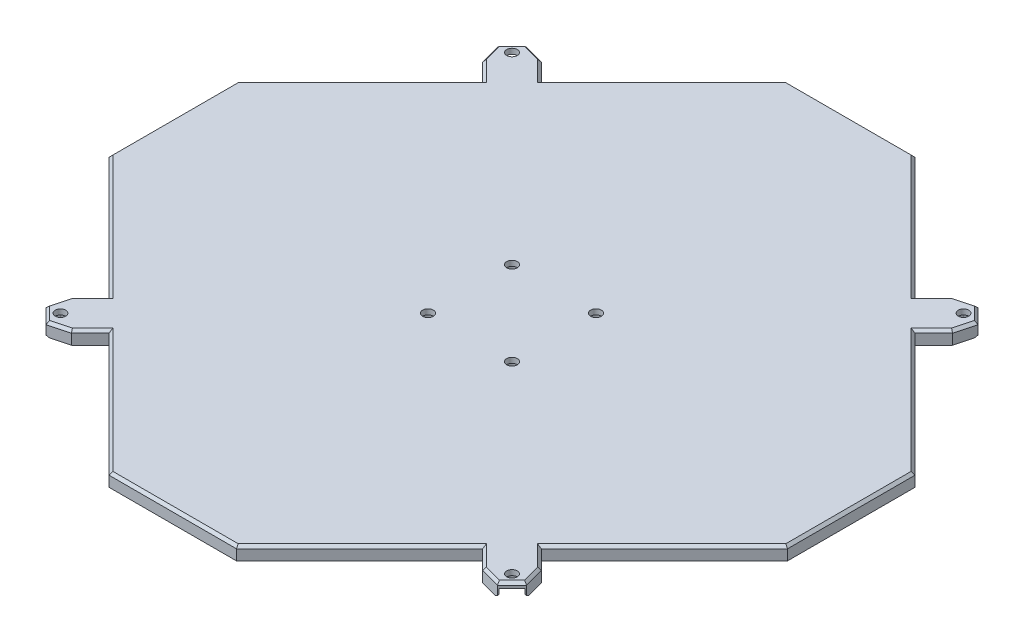
SolidWorks part; units mm, degrees
material "ABS"
ref_plane "Front Plane" through (0, 0, 0) normal (0, 0, 1) x (1, 0, 0)
ref_plane "Top Plane" through (0, 0, 0) normal (0, 1, 0) x (1, 0, 0)
ref_plane "Right Plane" through (0, 0, 0) normal (1, 0, 0) x (0, 0, -1)
sketch "Floor Reference" plane through (0, 0, 0) normal (0, 1, 0) x (-1, 0, 0)
  line L0 (-129.3223, 24.3223) -> (-82.4792, 71.1655)
  line L1 (-82.4792, 71.1655) -> (-89.601, 78.2873)
  line L2 (-89.601, 78.2873) -> (-91.6716, 86.0147)
  line L3 (-91.6716, 86.0147) -> (-86.0147, 91.6716)
  line L4 (-86.0147, 91.6716) -> (-78.2873, 89.601)
  line L5 (-78.2873, 89.601) -> (-71.1655, 82.4792)
  line L6 (-71.1655, 82.4792) -> (-24.3223, 129.3223)
  line L7 (-24.3223, 129.3223) -> (0, 129.3223)
  line L31 (-129.3223, 0) -> (-129.3223, 24.3223)
  line L32 (0, 0) -> (-35355.3391, 35355.3391) construction
  line L34 (-1000, 0) -> (0, 0) construction
  line L35 (0, 0) -> (0, 49000) construction
  circle A0 centre (-86.0147, 86.0147) radius 2
  point P8 (0, 0)
  point P14 (0, 0)
  point P18 (-88.8431, 88.8431)
  dimension "D11" = 4
  dimension "D1" = 105
  dimension "D2" = 45
  dimension "D3" = 129.3223
  dimension "D4" = 8
  dimension "D5" = 16
  dimension "D6" = 17
  dimension "D7" = 8
  dimension "D8" = 13
  dimension "D9" = 105
  dimension "D10" = 24.3223
sketch "Sketch2" plane through (0, 0, 0) normal (0, 1, 0) x (1, 0, 0)
  line L0 (129.3223, 0) -> (129.3223, -24.3223) construction
  line L1 (129.3223, -24.3223) -> (82.4792, -71.1655) construction
  line L2 (82.4792, -71.1655) -> (89.601, -78.2873) construction
  line L3 (89.601, -78.2873) -> (91.6716, -86.0147) construction
  line L4 (91.6716, -86.0147) -> (86.0147, -91.6716) construction
  line L5 (86.0147, -91.6716) -> (78.2873, -89.601) construction
  line L6 (78.2873, -89.601) -> (71.1655, -82.4792) construction
  line L7 (71.1655, -82.4792) -> (24.3223, -129.3223) construction
  line L8 (24.3223, -129.3223) -> (0, -129.3223) construction
  line L9 (129.3223, 0) -> (129.3223, -24.3223) construction
  line L10 (129.3223, -24.3223) -> (82.4792, -71.1655) construction
  line L11 (82.4792, -71.1655) -> (89.601, -78.2873) construction
  line L12 (89.601, -78.2873) -> (91.6716, -86.0147) construction
  line L13 (91.6716, -86.0147) -> (86.0147, -91.6716) construction
  line L14 (86.0147, -91.6716) -> (78.2873, -89.601) construction
  line L15 (78.2873, -89.601) -> (71.1655, -82.4792) construction
  line L16 (71.1655, -82.4792) -> (24.3223, -129.3223) construction
  line L17 (24.3223, -129.3223) -> (0, -129.3223) construction
  line L18 (-129.3223, -24.3223) -> (-129.3223, 0) construction
  line L19 (-82.4792, -71.1655) -> (-129.3223, -24.3223) construction
  line L20 (-89.601, -78.2873) -> (-82.4792, -71.1655) construction
  line L21 (-91.6716, -86.0147) -> (-89.601, -78.2873) construction
  line L22 (-86.0147, -91.6716) -> (-91.6716, -86.0147) construction
  line L23 (-78.2873, -89.601) -> (-86.0147, -91.6716) construction
  line L24 (-71.1655, -82.4792) -> (-78.2873, -89.601) construction
  line L25 (-24.3223, -129.3223) -> (-71.1655, -82.4792) construction
  line L26 (0, -129.3223) -> (-24.3223, -129.3223) construction
  line L27 (-24.3223, 129.3223) -> (0, 129.3223) construction
  line L28 (-71.1655, 82.4792) -> (-24.3223, 129.3223) construction
  line L29 (-78.2873, 89.601) -> (-71.1655, 82.4792) construction
  line L30 (-86.0147, 91.6716) -> (-78.2873, 89.601) construction
  line L31 (-91.6716, 86.0147) -> (-86.0147, 91.6716) construction
  line L32 (-89.601, 78.2873) -> (-91.6716, 86.0147) construction
  line L33 (-82.4792, 71.1655) -> (-89.601, 78.2873) construction
  line L34 (-129.3223, 24.3223) -> (-82.4792, 71.1655) construction
  line L35 (-129.3223, 0) -> (-129.3223, 24.3223) construction
  line L36 (129.3223, 24.3223) -> (129.3223, 0) construction
  line L37 (82.4792, 71.1655) -> (129.3223, 24.3223) construction
  line L38 (89.601, 78.2873) -> (82.4792, 71.1655) construction
  line L39 (91.6716, 86.0147) -> (89.601, 78.2873) construction
  line L40 (86.0147, 91.6716) -> (91.6716, 86.0147) construction
  line L41 (78.2873, 89.601) -> (86.0147, 91.6716) construction
  line L42 (71.1655, 82.4792) -> (78.2873, 89.601) construction
  line L43 (24.3223, 129.3223) -> (71.1655, 82.4792) construction
  line L44 (0, 129.3223) -> (24.3223, 129.3223) construction
  line L45 (129.2223, 0) -> (129.2223, -24.2809)
  line L46 (129.2223, -24.2809) -> (82.3378, -71.1655)
  line L47 (82.3378, -71.1655) -> (89.5114, -78.3391)
  line L48 (89.5114, -78.3391) -> (91.56, -85.9848)
  line L49 (91.56, -85.9848) -> (85.9848, -91.56)
  line L50 (85.9848, -91.56) -> (78.3391, -89.5114)
  line L51 (78.3391, -89.5114) -> (71.1655, -82.3378)
  line L52 (71.1655, -82.3378) -> (24.2809, -129.2223)
  line L53 (24.2809, -129.2223) -> (0, -129.2223)
  line L54 (0, -129.2223) -> (-24.2809, -129.2223)
  line L55 (-24.2809, -129.2223) -> (-71.1655, -82.3378)
  line L56 (-71.1655, -82.3378) -> (-78.3391, -89.5114)
  line L57 (-78.3391, -89.5114) -> (-85.9848, -91.56)
  line L58 (-85.9848, -91.56) -> (-91.56, -85.9848)
  line L59 (-91.56, -85.9848) -> (-89.5114, -78.3391)
  line L60 (-89.5114, -78.3391) -> (-82.3378, -71.1655)
  line L61 (-82.3378, -71.1655) -> (-129.2223, -24.2809)
  line L62 (-129.2223, -24.2809) -> (-129.2223, 0)
  line L63 (-129.2223, 0) -> (-129.2223, 24.2809)
  line L64 (-129.2223, 24.2809) -> (-82.3378, 71.1655)
  line L65 (-82.3378, 71.1655) -> (-89.5114, 78.3391)
  line L66 (-89.5114, 78.3391) -> (-91.56, 85.9848)
  line L67 (-91.56, 85.9848) -> (-85.9848, 91.56)
  line L68 (-85.9848, 91.56) -> (-78.3391, 89.5114)
  line L69 (-78.3391, 89.5114) -> (-71.1655, 82.3378)
  line L70 (-71.1655, 82.3378) -> (-24.2809, 129.2223)
  line L71 (-24.2809, 129.2223) -> (0, 129.2223)
  line L72 (0, 129.2223) -> (24.2809, 129.2223)
  line L73 (24.2809, 129.2223) -> (71.1655, 82.3378)
  line L74 (71.1655, 82.3378) -> (78.3391, 89.5114)
  line L75 (78.3391, 89.5114) -> (85.9848, 91.56)
  line L76 (85.9848, 91.56) -> (91.56, 85.9848)
  line L77 (91.56, 85.9848) -> (89.5114, 78.3391)
  line L78 (89.5114, 78.3391) -> (82.3378, 71.1655)
  line L79 (82.3378, 71.1655) -> (129.2223, 24.2809)
  line L80 (129.2223, 24.2809) -> (129.2223, 0)
  circle A0 centre (86.0147, -86.0147) radius 2 construction
  circle A1 centre (86.0147, -86.0147) radius 2
  circle A2 centre (-86.0147, -86.0147) radius 2
  circle A3 centre (-86.0147, 86.0147) radius 2
  circle A4 centre (86.0147, 86.0147) radius 2
  point P13 (0, 0)
  point P54 (0, 0)
  dimension "D2" = 0.1
  dimension "D1" = 4
extrude "Main Floor Extrude" add sketch "Sketch2" along normal blind 5
chamfer "Main Floor Chamfer" distance 1 angle 45 32 edges at (-74.7523, 5, -85.9246) (-82.162, 5, -90.5357) (-88.7724, 5, -88.7724) (-90.5357, 5, -82.162) (-85.9246, 5, -74.7523) (-47.7232, 5, -105.78) (0, 5, -129.2223) (47.7232, 5, -105.78) (74.7523, 5, -85.9246) (82.162, 5, -90.5357) (88.7724, 5, -88.7724) (90.5357, 5, -82.162) (85.9246, 5, -74.7523) (105.78, 5, -47.7232) (129.2223, 5, 0) (105.78, 5, 47.7232) (85.9246, 5, 74.7523) (90.5357, 5, 82.162) (88.7724, 5, 88.7724) (82.162, 5, 90.5357) (74.7523, 5, 85.9246) (47.7232, 5, 105.78) (0, 5, 129.2223) (-47.7232, 5, 105.78) (-74.7523, 5, 85.9246) (-82.162, 5, 90.5357) (-88.7724, 5, 88.7724) (-90.5357, 5, 82.162) (-85.9246, 5, 74.7523) (-105.78, 5, 47.7232) (-129.2223, 5, 0) (-105.78, 5, -47.7232)
sketch "Sketch3" plane through (0, 0, 0) normal (0, -1, 0) x (-1, 0, 0)
  line L0 (91.2473, -86.2976) -> (88.4896, -83.5398)
  line L1 (91.56, -85.9848) -> (85.9848, -91.56) construction
  line L2 (83.5398, -88.4896) -> (86.2976, -91.2473)
  line L3 (86.2976, -91.2473) -> (91.2473, -86.2976)
  line L4 (-86.2976, -91.2473) -> (-83.5398, -88.4896)
  line L5 (-88.4896, -83.5398) -> (-91.2473, -86.2976)
  line L6 (-91.2473, -86.2976) -> (-86.2976, -91.2473)
  line L7 (-91.2473, 86.2976) -> (-88.4896, 83.5398)
  line L8 (-83.5398, 88.4896) -> (-86.2976, 91.2473)
  line L9 (-86.2976, 91.2473) -> (-91.2473, 86.2976)
  line L10 (86.2976, 91.2473) -> (83.5398, 88.4896)
  line L11 (88.4896, 83.5398) -> (91.2473, 86.2976)
  line L12 (91.2473, 86.2976) -> (86.2976, 91.2473)
  arc A0 (88.4896, -83.5398) -> (83.5398, -88.4896) centre (86.0147, -86.0147) ccw
  arc A1 (83.5398, -88.4896) -> (88.4896, -83.5398) centre (86.0147, -86.0147) ccw construction
  arc A2 (-83.5398, -88.4896) -> (-88.4896, -83.5398) centre (-86.0147, -86.0147) ccw
  arc A3 (-88.4896, -83.5398) -> (-83.5398, -88.4896) centre (-86.0147, -86.0147) ccw construction
  arc A4 (-88.4896, 83.5398) -> (-83.5398, 88.4896) centre (-86.0147, 86.0147) ccw
  arc A5 (-83.5398, 88.4896) -> (-88.4896, 83.5398) centre (-86.0147, 86.0147) ccw construction
  arc A6 (83.5398, 88.4896) -> (88.4896, 83.5398) centre (86.0147, 86.0147) ccw
  arc A7 (88.4896, 83.5398) -> (83.5398, 88.4896) centre (86.0147, 86.0147) ccw construction
  point P1 (0, 0)
  point P9 (0, 0)
  point P10 (86.0147, 91.2473)
  point P28 (0, 0)
  dimension "D1" = 7
  dimension "D2" = 4
extrude "Mount Screw Countersink" cut sketch "Sketch3" against normal blind 3
chamfer "Mount Screw Countersink Chamfer" distance 1 angle 45 12 edges at (-84.9187, 0, -89.8685) (-89.8685, 0, -84.9187) (-83.5398, 0, -83.5398) (89.8685, 0, -84.9187) (84.9187, 0, -89.8685) (83.5398, 0, -83.5398) (84.9187, 0, 89.8685) (89.8685, 0, 84.9187) (83.5398, 0, 83.5398) (-89.8685, 0, 84.9187) (-84.9187, 0, 89.8685) (-83.5398, 0, 83.5398)
sketch "Sketch6" plane through (0, 5, 0) normal (0, 1, 0) x (1, 0, 0)
  line L1 (-16, -16) -> (16, -16) construction
  line L2 (-16, -16) -> (-16, 16) construction
  line L3 (-16, 16) -> (16, 16) construction
  line L4 (16, -16) -> (16, 16) construction
  line L5 (-16, -16) -> (16, 16) construction
  line L6 (-16, 16) -> (16, -16) construction
  circle A0 centre (-16, 16) radius 2.05
  circle A1 centre (16, 16) radius 2.05
  circle A2 centre (16, -16) radius 2.05
  circle A3 centre (-16, -16) radius 2.05
  point P0 (0, 0)
  dimension "D2" = 4.1
  dimension "D1" = 32
extrude "Bottom Motor Mount Holes" cut sketch "Sketch6" against normal through all
sketch "Sketch7" plane through (0, 0, 0) normal (0, -1, 0) x (-1, 0, 0)
  circle A0 centre (16, -16) radius 3.5
  circle A1 centre (-16, -16) radius 3.5
  circle A2 centre (-16, 16) radius 3.5
  circle A3 centre (16, 16) radius 3.5
  dimension "D1" = 7
extrude "Bottom Motor Mount Holes Countersink" cut sketch "Sketch7" against normal blind 3
